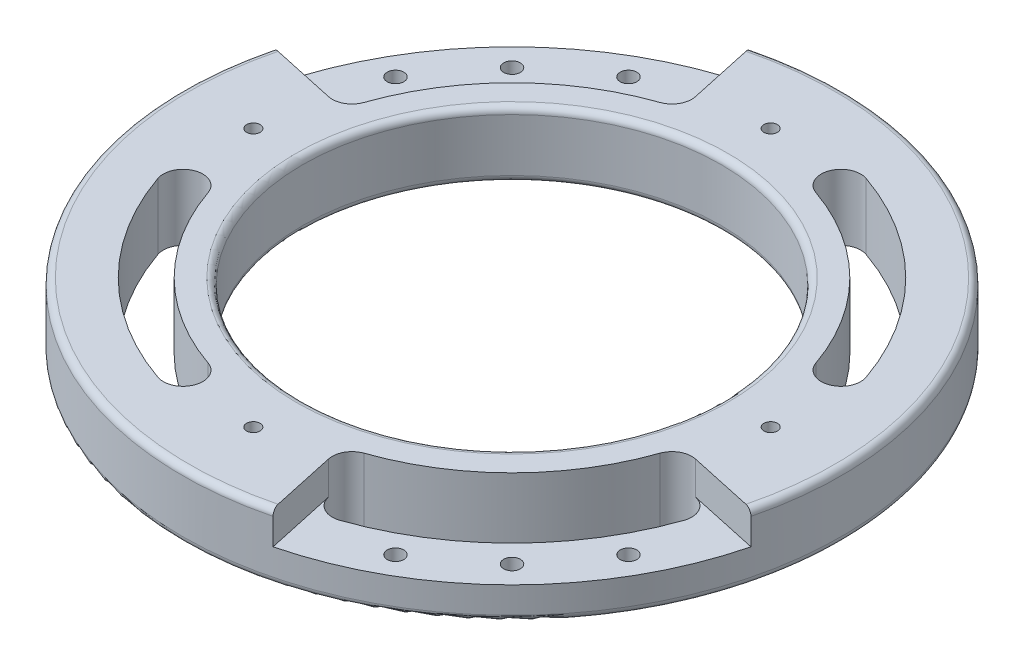
SolidWorks part; units mm, degrees
material "5052-H38"
ref_plane "Front Plane" through (0, 0, 0) normal (0, 0, 1) x (1, 0, 0)
ref_plane "Top Plane" through (0, 0, 0) normal (0, 1, 0) x (1, 0, 0)
ref_plane "Right Plane" through (0, 0, 0) normal (1, 0, 0) x (0, 0, -1)
sketch "Sketch1" plane through (0, 0, 0) normal (0, 1, 0) x (1, 0, 0)
  circle A0 centre (0, 0) radius 100
  circle A1 centre (0, 0) radius 78.5 construction
  circle A2 centre (-78.5, 0) radius 2.05
  circle A3 centre (0, 78.5) radius 2.05
  circle A4 centre (78.5, 0) radius 2.05
  circle A5 centre (0, -78.5) radius 2.05
  circle A6 centre (0, 0) radius 63.5
  arc A7 (-74.1943, 25.641) -> (-25.641, 74.1943) centre (0, 0) cw construction
  arc A8 (-27.6008, 79.8652) -> (-79.8652, 27.6008) centre (0, 0) ccw
  arc A9 (-23.6812, 68.5234) -> (-68.5234, 23.6812) centre (0, 0) ccw
  arc A10 (-23.6812, 68.5234) -> (-27.6008, 79.8652) centre (-25.641, 74.1943) ccw
  arc A11 (-79.8652, 27.6008) -> (-68.5234, 23.6812) centre (-74.1943, 25.641) ccw
  arc A12 (25.641, 74.1943) -> (74.1943, 25.641) centre (0, 0) cw construction
  arc A13 (79.8652, 27.6008) -> (27.6008, 79.8652) centre (0, 0) ccw
  arc A14 (68.5234, 23.6812) -> (23.6812, 68.5234) centre (0, 0) ccw
  arc A15 (68.5234, 23.6812) -> (79.8652, 27.6008) centre (74.1943, 25.641) ccw
  arc A16 (27.6008, 79.8652) -> (23.6812, 68.5234) centre (25.641, 74.1943) ccw
  arc A17 (74.1943, -25.641) -> (25.641, -74.1943) centre (0, 0) cw construction
  arc A18 (27.6008, -79.8652) -> (79.8652, -27.6008) centre (0, 0) ccw
  arc A19 (23.6812, -68.5234) -> (68.5234, -23.6812) centre (0, 0) ccw
  arc A20 (23.6812, -68.5234) -> (27.6008, -79.8652) centre (25.641, -74.1943) ccw
  arc A21 (79.8652, -27.6008) -> (68.5234, -23.6812) centre (74.1943, -25.641) ccw
  arc A22 (-25.641, -74.1943) -> (-74.1943, -25.641) centre (0, 0) cw construction
  arc A23 (-79.8652, -27.6008) -> (-27.6008, -79.8652) centre (0, 0) ccw
  arc A24 (-68.5234, -23.6812) -> (-23.6812, -68.5234) centre (0, 0) ccw
  arc A25 (-68.5234, -23.6812) -> (-79.8652, -27.6008) centre (-74.1943, -25.641) ccw
  arc A26 (-27.6008, -79.8652) -> (-23.6812, -68.5234) centre (-25.641, -74.1943) ccw
  point P15 (0, 0)
  point P17 (-55.5079, 55.5079)
  point P27 (55.5079, 55.5079)
  point P34 (55.5079, -55.5079)
  point P41 (-55.5079, -55.5079)
  point P46 (0, 0)
  dimension "D1" = 200
  dimension "D2" = 157
  dimension "D3" = 4.1
  dimension "D5" = 15
  dimension "D8" = 12
  dimension "D9" = 78.5
  dimension "D10" = 78.5
  dimension "D11" = 4
  dimension "D6" = 26
  dimension "D7" = 26
  dimension "D4" = 4
extrude "Boss-Extrude1" add sketch "Sketch1" along normal blind 20
fillet "Fillet1" radius 2 4 edges at (0, 0, 63.5) (0, 0, 100) (0, 20, 63.5) (0, 20, 100)
sketch "Sketch2" plane through (0, 20, 0) normal (0, 1, 0) x (1, 0, 0)
  line L0 (-19.7775, 75.467) -> (-24.4443, 96.9664)
  line L1 (-75.467, 19.7775) -> (-96.9664, 24.4443)
  line L2 (0, 0) -> (69.2965, 69.2965) construction
  line L3 (-78.5, 0) -> (78.5, 0) construction
  line L4 (19.7775, -75.467) -> (24.4443, -96.9664)
  line L5 (75.467, -19.7775) -> (96.9664, -24.4443)
  arc A0 (-79.8652, 27.6008) -> (-68.5234, 23.6812) centre (-74.1943, 25.641) ccw construction
  arc A1 (-75.467, 19.7775) -> (-68.5234, 23.6812) centre (-74.1943, 25.641) ccw
  arc A2 (-23.6812, 68.5234) -> (-68.5234, 23.6812) centre (0, 0) ccw construction
  arc A3 (-23.6812, 68.5234) -> (-27.6008, 79.8652) centre (-25.641, 74.1943) ccw construction
  arc A4 (-23.6812, 68.5234) -> (-68.5234, 23.6812) centre (0, 0) ccw
  arc A5 (-23.6812, 68.5234) -> (-19.7775, 75.467) centre (-25.641, 74.1943) ccw
  circle A6 centre (0, 0) radius 100 construction
  arc A7 (-24.4443, 96.9664) -> (-96.9664, 24.4443) centre (0, 0) ccw
  circle A8 centre (0, 0) radius 98 construction
  arc A9 (96.9664, -24.4443) -> (24.4443, -96.9664) centre (0, 0) cw
  arc A10 (19.7775, -75.467) -> (23.6812, -68.5234) centre (25.641, -74.1943) cw
  arc A11 (68.5234, -23.6812) -> (75.467, -19.7775) centre (74.1943, -25.641) cw
  arc A12 (68.5234, -23.6812) -> (23.6812, -68.5234) centre (0, 0) cw
  circle A13 centre (0, 0) radius 90 construction
  dimension "D4" = 180
  dimension "D1" = 22
  dimension "D2" = 22
  dimension "D3" = 45
extrude "Cut-Extrude1" cut sketch "Sketch2" against normal blind 10
sketch "Sketch3" plane through (0, 10, 0) normal (0, 1, 0) x (1, 0, 0)
  line L0 (-65.2306, 65.2306) -> (65.2306, -65.2306) construction
  line L1 (0, 0) -> (-92.25, 0) construction
  line L2 (0, 0) -> (57.2584, 57.2584) construction
  circle A0 centre (0, 0) radius 92.25 construction
  arc A1 (-24.4443, 96.9664) -> (-96.9664, 24.4443) centre (0, 0) ccw construction
  circle A3 centre (-45.1119, 80.4672) radius 2.525
  circle A4 centre (-65.2306, 65.2306) radius 2.525
  circle A5 centre (-80.4672, 45.1119) radius 2.525
  circle A6 centre (45.1119, -80.4672) radius 2.525
  circle A7 centre (65.2306, -65.2306) radius 2.525
  circle A8 centre (80.4672, -45.1119) radius 2.525
  dimension "D1" = 7.75
  dimension "D2" = 45
  dimension "D3" = 5.05
  dimension "D4" = 50
  dimension "D5" = 25
extrude "Cut-Extrude2" cut sketch "Sketch3" against normal blind 10
